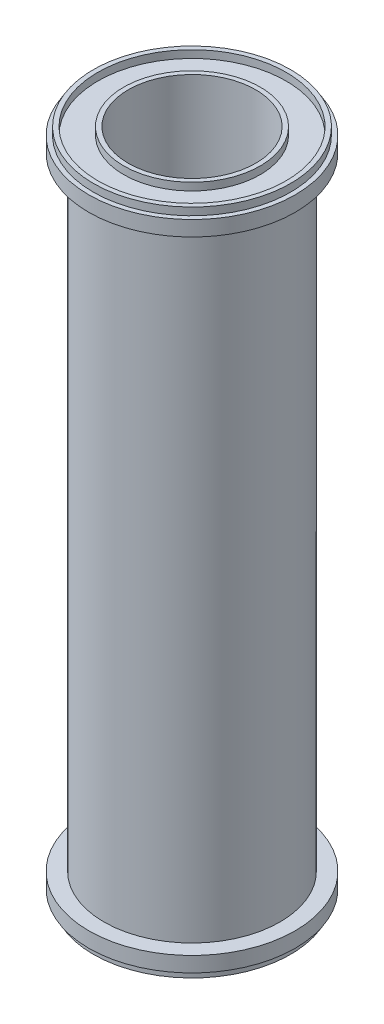
SolidWorks part; units mm, degrees
material "ASTM A36 Steel"
ref_plane "Front" through (0, 0, 0) normal (0, 0, 1) x (1, 0, 0)
ref_plane "Top" through (0, 0, 0) normal (0, 1, 0) x (1, 0, 0)
ref_plane "Right" through (0, 0, 0) normal (1, 0, 0) x (0, 0, -1)
ref_plane "Plane1" through (0, 0, 0) normal (0, -1, 0) x (1, 0, 0)
sketch "Sketch1" plane through (0, 0, 0) normal (1, 0, 0) x (0, 1, 0)
  line L0 (22, 4.5) -> (22, 4.2)
  line L1 (21.5, 4.5) -> (22, 4.5)
  line L2 (21.5, 6.2) -> (21.5, 4.5)
  line L3 (22, 6.2) -> (21.5, 6.2)
  line L4 (22, 6.5) -> (22, 6.2)
  line L5 (21.5, 6.5) -> (22, 6.5)
  line L6 (21.5, 6.8) -> (21.5, 6.5)
  line L7 (20.5, 6.8) -> (21.5, 6.8)
  line L8 (20.5, 5.8) -> (20.5, 6.8)
  line L9 (20.5, 5.8) -> (-20.5, 5.8)
  line L10 (-20.5, 5.8) -> (-20.5, 6.8)
  line L11 (-20.5, 6.8) -> (-21.5, 6.8)
  line L12 (-21.5, 6.8) -> (-21.5, 6.5)
  line L13 (-21.5, 6.5) -> (-22, 6.5)
  line L14 (-22, 6.5) -> (-22, 6.2)
  line L15 (-22, 6.2) -> (-21.5, 6.2)
  line L16 (-21.5, 6.2) -> (-21.5, 4.5)
  line L17 (-21.5, 4.5) -> (-22, 4.5)
  line L18 (-22, 4.5) -> (-22, 4.2)
  line L19 (-22, 4.2) -> (22, 4.2)
  line L20 (0, 0) -> (11.5, 0) construction
  line L21 (0, 0) -> (0, 8.7484) construction
  dimension "D1" = 8.4
  dimension "D2" = 11.6
  dimension "D3" = 44
  dimension "D4" = 0.5
  dimension "D5" = 1
  dimension "D6" = 13.6
  dimension "D7" = 0.3
  dimension "D8" = 1.7
revolve "Revolve1" add sketch "Sketch1" angle 360 about L20
